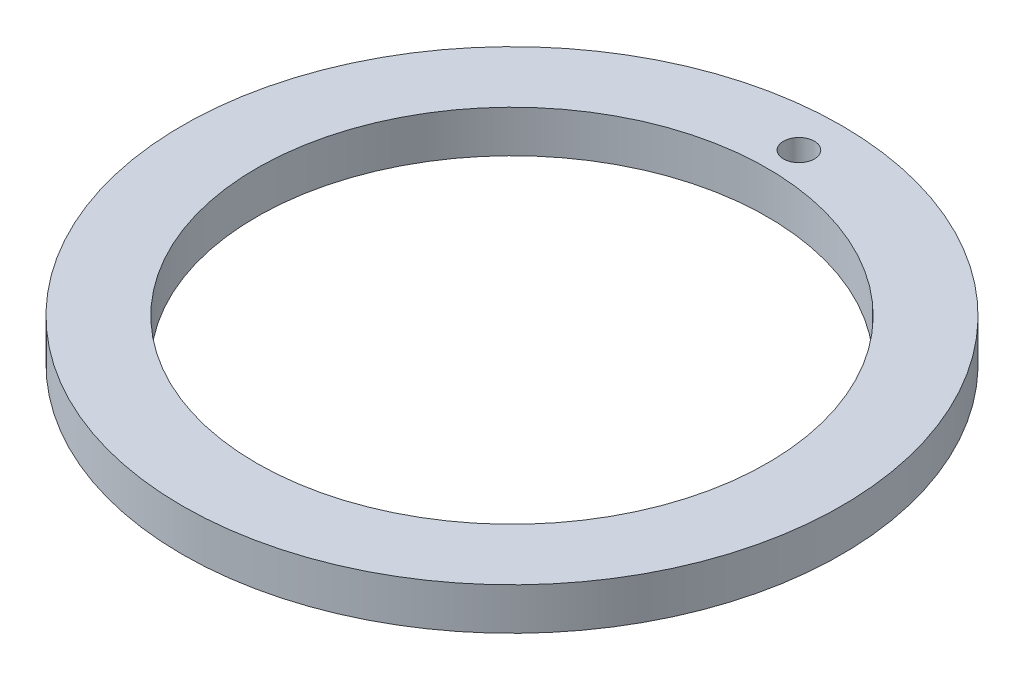
SolidWorks part; units mm, degrees
ref_plane "Front Plane" through (0, 0, 0) normal (0, 0, 1) x (1, 0, 0)
ref_plane "Top Plane" through (0, 0, 0) normal (0, 1, 0) x (1, 0, 0)
ref_plane "Right Plane" through (0, 0, 0) normal (1, 0, 0) x (0, 0, -1)
sketch "Sketch1" plane through (0, 0, 0) normal (0, 1, 0) x (1, 0, 0)
  line L0 (0, 0) -> (0, 44.2277) construction
  circle A0 centre (0, 0) radius 50.8
  circle A1 centre (0, 0) radius 39.37
  circle A2 centre (0, 44.2277) radius 2.3812
  dimension "D1" = 101.6
  dimension "D2" = 78.74
  dimension "D3" = 4.7625
  dimension "D4" = 44.2277
extrude "Boss-Extrude1" add sketch "Sketch1" along normal blind 6.477
